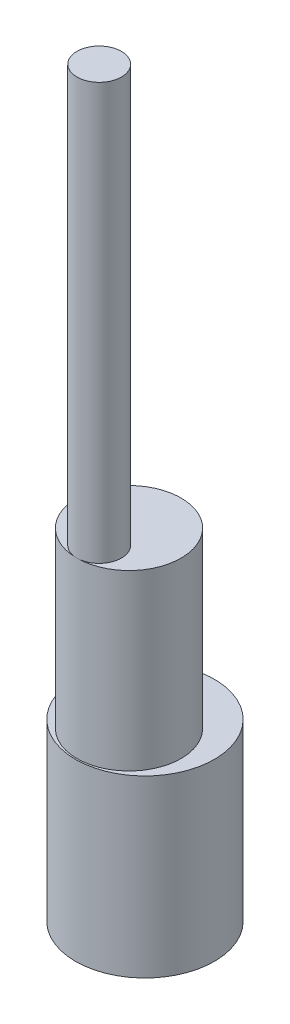
SolidWorks part; units mm, degrees
ref_plane "Front Plane" through (0, 0, 0) normal (0, 0, 1) x (1, 0, 0)
ref_plane "Top Plane" through (0, 0, 0) normal (0, 1, 0) x (1, 0, 0)
ref_plane "Right Plane" through (0, 0, 0) normal (1, 0, 0) x (0, 0, -1)
sketch "Sketch2" plane through (0, 0, 0) normal (0, 1, 0) x (1, 0, 0)
  line L0 (0, -55) -> (0, 55) construction
  circle A0 centre (0, -1249.8347) radius 500
  dimension "D1" = 1000
extrude "Boss-Extrude1" add sketch "Sketch2" along normal blind 1250 and the other way blind 10
sketch "Sketch3" plane through (0, 1250, 0) normal (0, 1, 0) x (1, 0, 0)
  line L0 (0, -550) -> (0, 550) construction
  circle A0 centre (0, -1364.6351) radius 375
  dimension "D1" = 750
extrude "Boss-Extrude2" add sketch "Sketch3" along normal blind 1250
sketch "Sketch5" plane through (0, 2500, 0) normal (0, 1, 0) x (1, 0, 0)
  circle A0 centre (0, -1579.4156) radius 160.2195
extrude "Boss-Extrude3" add sketch "Sketch5" along normal blind 3000
